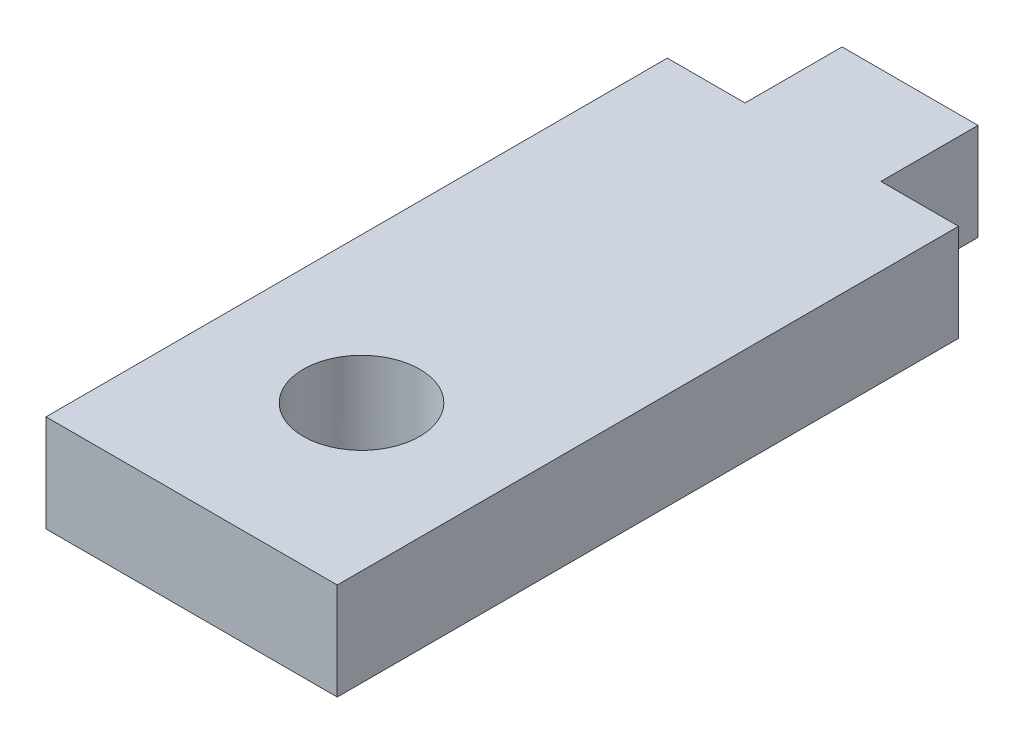
SolidWorks part; units mm, degrees
material "Acrylic (Medium-high impact)"
ref_plane "Front Plane" through (0, 0, 0) normal (0, 0, 1) x (1, 0, 0)
ref_plane "Top Plane" through (0, 0, 0) normal (0, 1, 0) x (1, 0, 0)
ref_plane "Right Plane" through (0, 0, 0) normal (1, 0, 0) x (0, 0, -1)
sketch "Sketch1" plane through (0, 0, 0) normal (0, 1, 0) x (1, 0, 0)
  line L0 (-7.5, -16) -> (-7.5, 16)
  line L1 (-7.5, 16) -> (-3.5, 16)
  line L2 (-3.5, 16) -> (-3.5, 21)
  line L3 (-3.5, 21) -> (3.5, 21)
  line L4 (3.5, 21) -> (3.5, 16)
  line L5 (3.5, 16) -> (7.5, 16)
  line L6 (7.5, 16) -> (7.5, -16)
  line L7 (7.5, -16) -> (-7.5, -16)
  point P9 (0, 21)
  point P10 (0, -16)
  point P12 (-7.5, 0)
  dimension "D1" = 15
  dimension "D2" = 37
  dimension "D3" = 5
  dimension "D4" = 7
extrude "Boss-Extrude1" add sketch "Sketch1" along normal blind 5
sketch "Sketch2" plane through (0, 5, 0) normal (0, 1, 0) x (1, 0, 0)
  line L0 (-3.5, 16) -> (-7.5, 16) construction
  circle A0 centre (0, -7.25) radius 3
  dimension "D1" = 23.25
  dimension "D2" = 6
extrude "Cut-Extrude1" cut sketch "Sketch2" against normal blind 10
